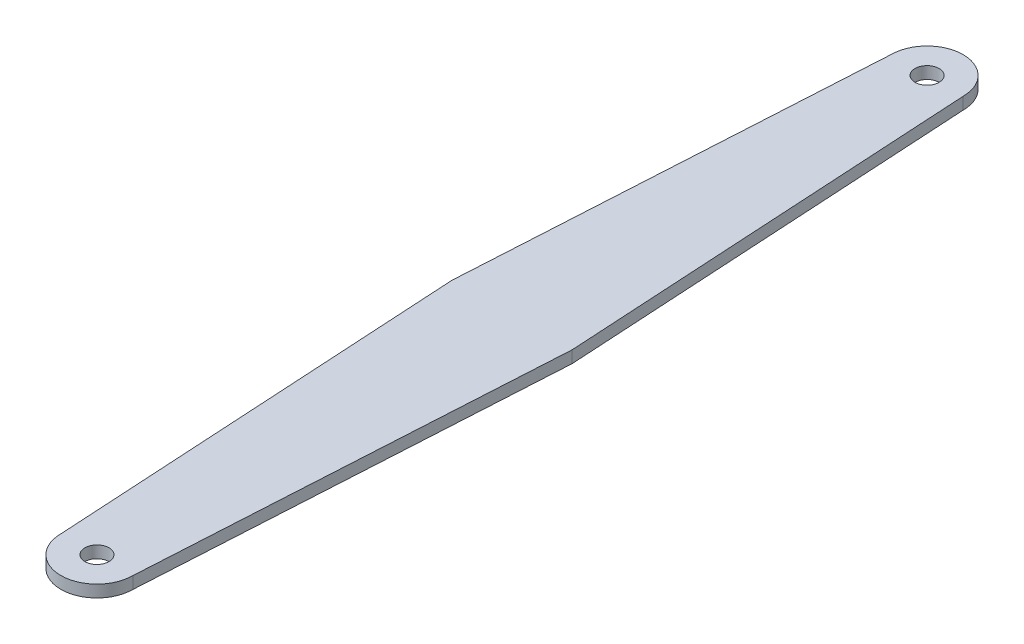
SolidWorks part; units mm, degrees
ref_plane "Front Plane" through (0, 0, 0) normal (0, 0, 1) x (1, 0, 0)
ref_plane "Top Plane" through (0, 0, 0) normal (0, 1, 0) x (1, 0, 0)
ref_plane "Right Plane" through (0, 0, 0) normal (1, 0, 0) x (0, 0, -1)
sketch "Sketch1" plane through (0, 0, 0) normal (0, 1, 0) x (1, 0, 0)
  line L0 (20, 345) -> (0, 0)
  line L1 (99.3995, 375) -> (678.4638, 375) construction
  line L2 (0, 0) -> (20, -345)
  line L3 (99.3995, -375) -> (1194.396, -375) construction
  line L4 (80, -345) -> (100, 0)
  line L5 (100, 0) -> (80, 345)
  line L6 (0, 0) -> (100, 0) construction
  line L7 (20, -345) -> (80, -345) construction
  line L8 (20, 345) -> (80, 345) construction
  arc A0 (20, 345) -> (80, 345) centre (50, 345) cw
  arc A1 (20, -345) -> (80, -345) centre (50, -345) ccw
  dimension "D1" = 750
  dimension "D2" = 100
  dimension "D3" = 60
extrude "Boss-Extrude1" add sketch "Sketch1" along normal blind 10
sketch "Sketch2" plane through (0, 10, 0) normal (0, 1, 0) x (1, 0, 0)
  line L0 (-119.1988, 0) -> (628.2932, 0) construction
  circle A0 centre (50, -345) radius 10
  arc A1 (20, -345) -> (80, -345) centre (50, -345) ccw construction
  circle A2 centre (50, 345) radius 10
  dimension "D1" = 20
extrude "Cut-Extrude1" cut sketch "Sketch2" against normal blind 10
